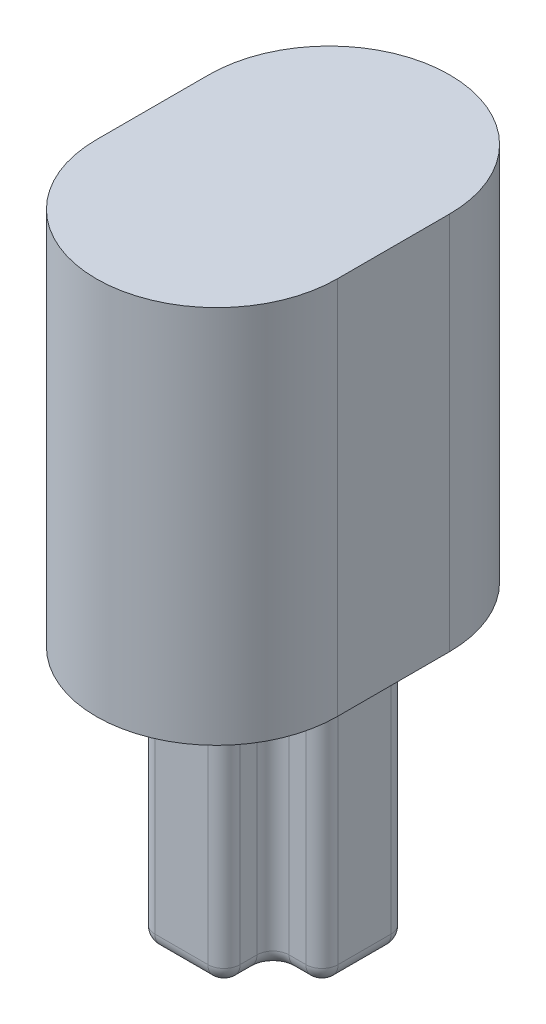
SolidWorks part; units mm, degrees
ref_plane "Front Plane" through (0, 0, 0) normal (0, 0, 1) x (1, 0, 0)
ref_plane "Top Plane" through (0, 0, 0) normal (0, 1, 0) x (1, 0, 0)
ref_plane "Right Plane" through (0, 0, 0) normal (1, 0, 0) x (0, 0, -1)
sketch "Sketch8" plane through (-2.2328, 0, 0.6657) normal (0, -1, 0) x (-1, 0, 0)
  line L0 (-26.6943, -20.8278) -> (-26.6943, -22.3528)
  line L9 (-28.2193, -19.5778) -> (-26.6943, -19.5778)
  line L10 (-28.2193, -19.5778) -> (-28.2193, -20.8278)
  line L11 (-28.2193, -20.8278) -> (-26.6943, -20.8278)
  line L12 (-23.9193, -19.5778) -> (-23.9193, -20.8278)
  line L13 (-28.2193, -19.5778) -> (-23.9193, -20.8278) construction
  line L14 (-28.2193, -20.8278) -> (-23.9193, -19.5778) construction
  line L15 (-26.6943, -18.0528) -> (-25.4443, -18.0528)
  line L16 (-26.6943, -18.0528) -> (-26.6943, -19.5778)
  line L17 (-26.6943, -22.3528) -> (-25.4443, -22.3528)
  line L18 (-25.4443, -18.0528) -> (-25.4443, -19.5778)
  line L19 (-26.6943, -18.0528) -> (-25.4443, -22.3528) construction
  line L20 (-26.6943, -22.3528) -> (-25.4443, -18.0528) construction
  line L21 (-25.4443, -20.8278) -> (-25.4443, -22.3528)
  line L22 (-25.4443, -19.5778) -> (-23.9193, -19.5778)
  line L23 (-25.4443, -20.8278) -> (-23.9193, -20.8278)
  line L25 (-24.7443, -18.8778) -> (-23.2193, -18.8778)
  line L26 (-23.2193, -18.8778) -> (-23.2193, -21.5278)
  line L27 (-24.7443, -21.5278) -> (-23.2193, -21.5278)
  line L28 (-24.7443, -21.5278) -> (-24.7443, -23.0528)
  line L29 (-27.3943, -23.0528) -> (-24.7443, -23.0528)
  line L30 (-27.3943, -21.5278) -> (-27.3943, -23.0528)
  line L31 (-28.9193, -21.5278) -> (-27.3943, -21.5278)
  line L32 (-28.9193, -18.8778) -> (-28.9193, -21.5278)
  line L33 (-28.9193, -18.8778) -> (-27.3943, -18.8778)
  line L34 (-27.3943, -17.3528) -> (-27.3943, -18.8778)
  line L35 (-27.3943, -17.3528) -> (-24.7443, -17.3528)
  line L36 (-24.7443, -17.3528) -> (-24.7443, -18.8778)
  point P0 (-26.0693, -20.2028)
  point P5 (-26.0693, -20.2028)
  point P10 (-26.0693, -20.2028)
  point P35 (4.0539, 0.4)
  point P37 (-23.2193, -20.2028)
  point P38 (-23.2193, -20.2028)
  dimension "D1" = 1.25
  dimension "D2" = 4.3
  dimension "D3" = 1.25
  dimension "D4" = 4.3
  dimension "D5" = 0.7
extrude "Boss-Extrude1" add sketch "Sketch8" along normal blind 8.1
sketch "Sketch9" plane through (0, 0, 0) normal (0, 1, 0) x (-1, 0, 0)
  line L0 (-23.8366, 22.6185) -> (-23.8366, 19.1185) construction
  line L1 (-20.0866, 22.6185) -> (-20.0866, 19.1185)
  line L2 (-27.5866, 22.6185) -> (-27.5866, 19.1185)
  line L3 (-25.1616, 22.1935) -> (-22.5116, 19.5435) construction
  line L15 (-22.5116, 18.0185) -> (-22.5116, 19.5435)
  line L16 (-22.5116, 19.5435) -> (-20.9866, 19.5435)
  line L17 (-20.9866, 19.5435) -> (-20.9866, 22.1935)
  line L18 (-20.9866, 22.1935) -> (-22.5116, 22.1935)
  line L19 (-22.5116, 22.1935) -> (-22.5116, 23.7185)
  line L20 (-22.5116, 23.7185) -> (-25.1616, 23.7185)
  line L21 (-25.1616, 23.7185) -> (-25.1616, 22.1935)
  line L22 (-25.1616, 22.1935) -> (-26.6866, 22.1935)
  line L23 (-26.6866, 22.1935) -> (-26.6866, 19.5435)
  line L24 (-26.6866, 19.5435) -> (-25.1616, 19.5435)
  line L25 (-25.1616, 19.5435) -> (-25.1616, 18.0185)
  line L26 (-25.1616, 18.0185) -> (-22.5116, 18.0185)
  line L27 (-22.5116, 18.0185) -> (-22.5116, 19.5435) construction
  line L28 (-22.5116, 19.5435) -> (-20.9866, 19.5435) construction
  line L29 (-20.9866, 19.5435) -> (-20.9866, 22.1935) construction
  line L30 (-20.9866, 22.1935) -> (-22.5116, 22.1935) construction
  line L31 (-22.5116, 22.1935) -> (-22.5116, 23.7185) construction
  line L32 (-22.5116, 23.7185) -> (-25.1616, 23.7185) construction
  line L33 (-25.1616, 23.7185) -> (-25.1616, 22.1935) construction
  line L34 (-25.1616, 22.1935) -> (-26.6866, 22.1935) construction
  line L35 (-26.6866, 22.1935) -> (-26.6866, 19.5435) construction
  line L36 (-26.6866, 19.5435) -> (-25.1616, 19.5435) construction
  line L37 (-25.1616, 19.5435) -> (-25.1616, 18.0185) construction
  line L38 (-25.1616, 18.0185) -> (-22.5116, 18.0185) construction
  arc A1 (-20.0866, 22.6185) -> (-27.5866, 22.6185) centre (-23.8366, 22.6185) ccw
  arc A2 (-27.5866, 19.1185) -> (-20.0866, 19.1185) centre (-23.8366, 19.1185) ccw
  point P5 (-23.8366, 20.8685)
  point P10 (-23.8366, 20.8685)
  dimension "D1" = 7.5
  dimension "D3" = 3.5
  dimension "D2" = 0
extrude "Boss-Extrude2" add sketch "Sketch9" along normal blind 11.8
fillet "Fillet1" radius 0.5 12 edges at (22.5116, -4.05, 19.5435) (20.9866, -4.05, 19.5435) (20.9866, -4.05, 22.1935) (22.5116, -4.05, 22.1935) (22.5116, -4.05, 23.7185) (25.1616, -4.05, 23.7185) (25.1616, -4.05, 22.1935) (26.6866, -4.05, 22.1935) (26.6866, -4.05, 19.5435) (25.1616, -4.05, 19.5435) (22.5116, -4.05, 18.0185) (25.1616, -4.05, 18.0185)
fillet "Fillet2" radius 0.5 24 edges at (22.5116, 0, 18.781) (22.658, 0, 18.1649) (23.8366, 0, 18.0185) (25.0151, 0, 18.1649) (25.1616, 0, 18.781) (25.308, 0, 19.397) (25.9241, 0, 19.5435) (26.5401, 0, 19.6899) (26.6866, 0, 20.8685) (26.5401, 0, 22.047) (25.9241, 0, 22.1935) (25.308, 0, 22.3399) (25.1616, 0, 22.956) (25.0151, 0, 23.572) (23.8366, 0, 23.7185) (22.658, 0, 23.572) (22.5116, 0, 22.956) (22.3651, 0, 22.3399) (21.7491, 0, 22.1935) (21.133, 0, 22.047) (20.9866, 0, 20.8685) (21.133, 0, 19.6899) (21.7491, 0, 19.5435) (22.3651, 0, 19.397)
fillet "Fillet4" radius 0.5 24 edges at (25.0151, -8.1, 23.572) (25.1616, -8.1, 22.956) (25.308, -8.1, 22.3399) (25.9241, -8.1, 22.1935) (26.5401, -8.1, 22.047) (26.6866, -8.1, 20.8685) (26.5401, -8.1, 19.6899) (25.9241, -8.1, 19.5435) (25.308, -8.1, 19.397) (25.1616, -8.1, 18.781) (25.0151, -8.1, 18.1649) (23.8366, -8.1, 18.0185) (22.658, -8.1, 18.1649) (22.5116, -8.1, 18.781) (22.3651, -8.1, 19.397) (21.7491, -8.1, 19.5435) (21.133, -8.1, 19.6899) (20.9866, -8.1, 20.8685) (21.133, -8.1, 22.047) (21.7491, -8.1, 22.1935) (22.3651, -8.1, 22.3399) (22.5116, -8.1, 22.956) (22.658, -8.1, 23.572) (23.8366, -8.1, 23.7185)
equation "\"baseLength\"= 18"
equation "\"firstLoftL\"= \"baseLength\" - 0.25"
equation "\"topSide\"= \"baseWidth\" - 3"
equation "\"topBtm\"= \"baseLength\" - 6"
equation "\"offset\"= 1"
equation "\"firstLoftH\"= 1.8"
equation "\"secLoftH\"= 9.5"
equation "\"baseWidth\"= 18"
equation "\"firstLoftW\"= \"baseWidth\" - 0.25"
equation "\"surfaceCurve\"= 60"
